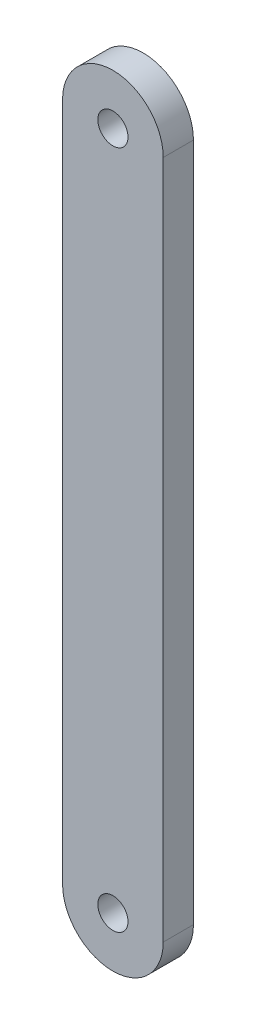
SolidWorks part; units mm, degrees
ref_plane "Front Plane" through (0, 0, 0) normal (0, 0, 1) x (1, 0, 0)
ref_plane "Top Plane" through (0, 0, 0) normal (0, 1, 0) x (1, 0, 0)
ref_plane "Right Plane" through (0, 0, 0) normal (1, 0, 0) x (0, 0, -1)
sketch "Sketch1" plane through (0, 0, 0) normal (0, 0, 1) x (1, 0, 0)
  line L0 (-5, 0) -> (-5, 67.5)
  line L1 (5, 67.5) -> (5, 0)
  circle A0 centre (0, 67.5) radius 1.5
  circle A1 centre (0, 0) radius 1.5
  circle A2 centre (0, 0) radius 5
  circle A3 centre (0, 67.5) radius 5
  line B0 (0, 0) -> (0, 67.5) construction
  dimension "D1" = 3
  dimension "D2" = 10
sketch_block_instance "Link 2-1"
sketch_block "Link 2"
extrude "Boss-Extrude1" add sketch "Sketch1" along normal blind 3 contours A3 L0 A2 L1 | A3 A0 | A2 A1
